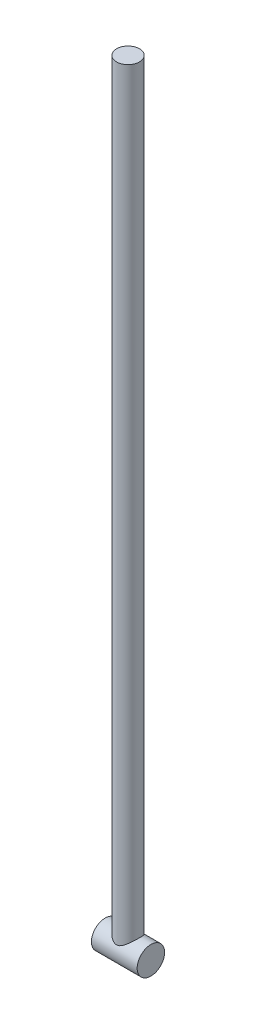
SolidWorks part; units mm, degrees
ref_plane "Front Plane" through (0, 0, 0) normal (0, 0, 1) x (1, 0, 0)
ref_plane "Top Plane" through (0, 0, 0) normal (0, 1, 0) x (1, 0, 0)
ref_plane "Right Plane" through (0, 0, 0) normal (1, 0, 0) x (0, 0, -1)
sketch "Sketch1" plane through (0, 0, 0) normal (0, 0, 1) x (1, 0, 0)
  line L0 (0, 4287.774) -> (0, 0)
  line L1 (-63.5, 0) -> (63.5, 0)
  line L2 (-63.5, 0) -> (-63.5, 4287.774)
  line L3 (-63.5, 4287.774) -> (63.5, 4287.774)
  line L4 (63.5, 0) -> (63.5, 4287.774)
  line L5 (0, -497.84) -> (0, 497.84) construction
  point P4 (0, 0)
  point P9 (0, 0)
  point P10 (0, 4287.774)
  point P12 (0, 0)
  dimension "D1" = 995.68
  dimension "D2" = 127
  dimension "D3" = 4785.614
revolve "Revolve1" add sketch "Sketch1" angle 360 about L0
sketch "Sketch2" plane through (0, 0, 0) normal (0, 0, 1) x (1, 0, 0)
  line L0 (-127, 0) -> (127, 0)
  line L1 (-127, 76.2) -> (127, 76.2)
  line L2 (-127, 76.2) -> (-127, -76.2)
  line L3 (-127, -76.2) -> (127, -76.2)
  line L4 (127, 76.2) -> (127, -76.2)
  point P6 (0, 0)
  dimension "D1" = 152.4
  dimension "D2" = 254
revolve "Revolve2" add sketch "Sketch2" angle 360 about L0
